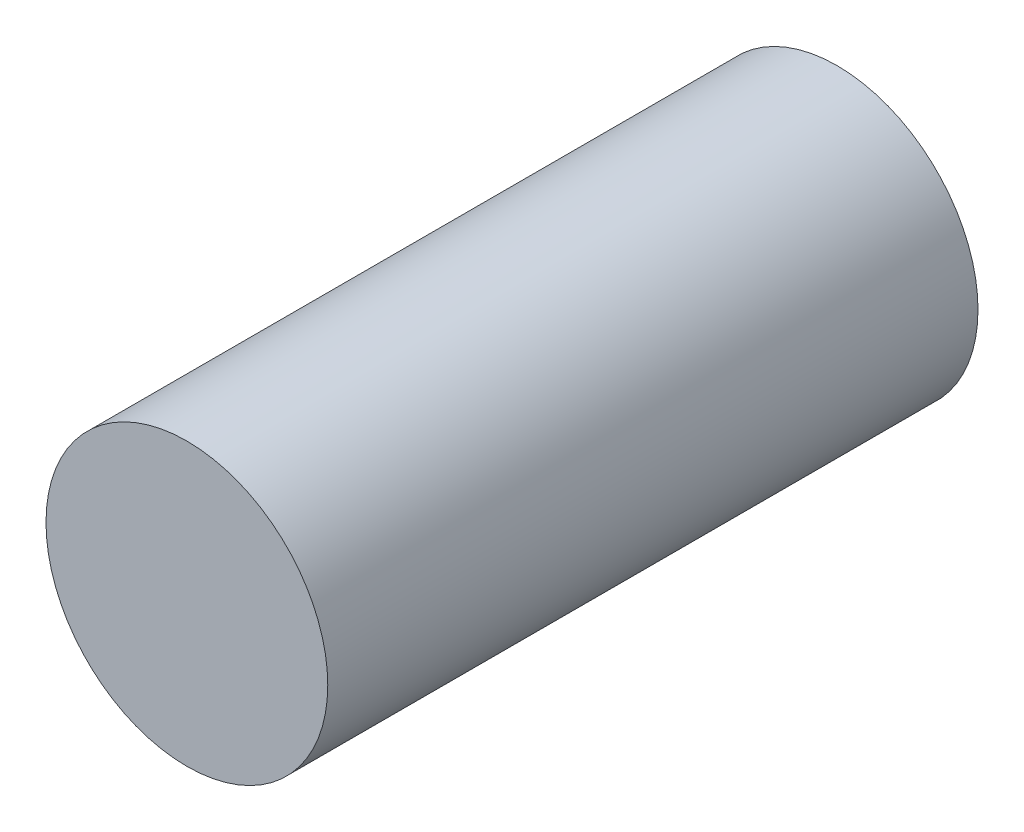
SolidWorks part; units mm, degrees
ref_plane "Front Plane" through (0, 0, 0) normal (0, 0, 1) x (1, 0, 0)
ref_plane "Top Plane" through (0, 0, 0) normal (0, 1, 0) x (1, 0, 0)
ref_plane "Right Plane" through (0, 0, 0) normal (1, 0, 0) x (0, 0, -1)
sketch "Sketch1" plane through (0, 0, 0) normal (0, 0, 1) x (1, 0, 0)
  circle A0 centre (0, 0) radius 32.5
  dimension "D1" = 65
extrude "Boss-Extrude1" add sketch "Sketch1" along normal blind 150
